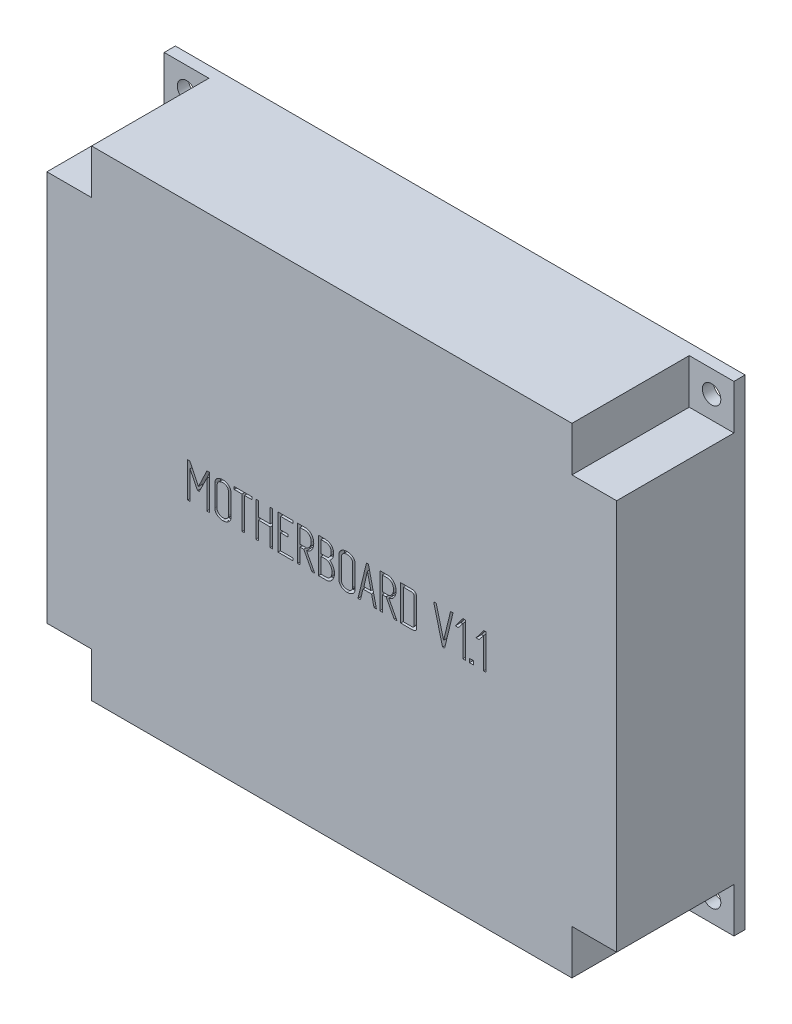
SolidWorks part; units mm, degrees
ref_plane "Front Plane" through (0, 0, 0) normal (0, 0, 1) x (1, 0, 0)
ref_plane "Top Plane" through (0, 0, 0) normal (0, 1, 0) x (1, 0, 0)
ref_plane "Right Plane" through (0, 0, 0) normal (1, 0, 0) x (0, 0, -1)
ref_plane "Plane1" through (0, 0, 23) normal (0, 0, 1) x (1, 0, 0)
sketch "Sketch1" plane through (0, 0, 23) normal (0, 0, 1) x (1, 0, 0)
  line L0 (55.1999, 44.7838) -> (30.0513, 44.7838)
  line L1 (30.0513, 40.8858) -> (30.0513, 40.8761)
  line L2 (30.0513, 40.8761) -> (55.1999, 40.8761)
  spline S0 degree 3 poles (30.0513, 40.8858) (30.0513, 42.1851) (30.0513, 43.4844) (30.0513, 44.7838) knots 0.259336 0.259336 0.259336 0.259336 0.499071 0.499071 0.499071 0.499071
  spline S1 degree 3 poles (55.1999, 44.7838) (55.1999, 43.4812) (55.1999, 42.1787) (55.1999, 40.8761) knots 0.759666 0.759666 0.759666 0.759666 1 1 1 1
extrude "Boss-Extrude1" add sketch "Sketch1" against normal blind 1
sketch "Sketch2" plane through (0, 0, 22) normal (0, 0, -1) x (-1, 0, 0)
  line L0 (-30.0513, 44.7838) -> (-30.0513, 40.8761)
  line L1 (-30.0513, 40.8761) -> (-55.1999, 40.8761)
  line L2 (-55.1999, 40.8761) -> (-55.1999, 44.7838)
  line L3 (-55.1999, 44.7838) -> (-30.0513, 44.7838)
extrude "Boss-Extrude2" add sketch "Sketch2" along normal blind 22
sketch "Sketch3" plane through (0, 44.7838, 0) normal (0, 1, 0) x (-1, 0, 0)
  line L0 (-55.1999, 23) -> (-30.0513, 23)
  line L1 (-30.0513, 23) -> (-30.0513, 0)
  line L2 (-30.0513, 0) -> (-55.1999, 0)
  line L3 (-55.1999, 0) -> (-55.1999, 23)
extrude "Boss-Extrude3" add sketch "Sketch3" along normal blind 1.1962
sketch "Sketch4" plane through (0, 40.8761, 0) normal (0, -1, 0) x (1, 0, 0)
  line L0 (30.0513, 23) -> (55.1999, 23)
  line L1 (55.1999, 23) -> (55.1999, 0)
  line L2 (55.1999, 0) -> (30.0513, 0)
  line L3 (30.0513, 0) -> (30.0513, 23)
extrude "Boss-Extrude4" add sketch "Sketch4" along normal blind 1.2185
sketch "Sketch5" plane through (0, 0, 23) normal (0, 0, 1) x (1, 0, 0)
  line L0 (31.4888, 39.6576) -> (31.545, 39.6576)
  line L1 (31.8363, 45.98) -> (31.1875, 45.98)
  spline S0 degree 3 poles (31.8363, 45.98) (32.0783, 45.9341) (32.298, 45.8314) (32.4985, 45.6785) (32.8054, 45.4444) (32.9531, 45.1417) (32.9531, 44.7838) (32.9531, 43.4812) (32.9531, 42.1787) (32.9531, 40.8761) (32.9531, 40.5134) (32.8032, 40.2135) (32.4985, 39.9814) (32.2203, 39.7694) (31.9055, 39.6628) (31.545, 39.6576) knots 0.649922 0.649922 0.649922 0.649922 0.695537 0.695537 0.695537 0.759638 0.759638 0.759638 1 1 1 1.064152 1.064152 1.064152 1.128028 1.128028 1.128028 1.128028
  spline S1 degree 3 poles (30.0513, 44.7838) (30.0513, 45.1755) (30.2109, 45.4899) (30.535, 45.722) (30.7214, 45.8555) (30.9397, 45.94) (31.1875, 45.98) knots 0.499071 0.499071 0.499071 0.499071 0.566736 0.566736 0.566736 0.611656 0.611656 0.611656 0.611656
  spline S2 degree 3 poles (30.0513, 40.8858) (30.0513, 42.1851) (30.0513, 43.4844) (30.0513, 44.7838) knots 0.259336 0.259336 0.259336 0.259336 0.499071 0.499071 0.499071 0.499071
  spline S3 degree 3 poles (31.4888, 39.6576) (31.1323, 39.6628) (30.8081, 39.7694) (30.5253, 39.9862) (30.2105, 40.2275) (30.0513, 40.5279) (30.0513, 40.8858) knots 0.131331 0.131331 0.131331 0.131331 0.194377 0.194377 0.194377 0.259336 0.259336 0.259336 0.259336
extrude "Cut-Extrude1" cut sketch "Sketch5" against normal blind 1
sketch "Sketch6" plane through (0, 0, 22) normal (0, 0, 1) x (1, 0, 0)
  spline S0 degree 3 poles (30.4866, 44.6967) (30.4866, 43.4522) (30.4866, 42.2077) (30.4866, 40.9631) (30.4866, 40.6971) (30.6172, 40.4795) (30.8783, 40.3151) (31.0918, 40.1807) (31.3088, 40.112) (31.7682, 40.112) (31.981, 40.1748) (32.1696, 40.3102) (32.3897, 40.4683) (32.4985, 40.6826) (32.4985, 40.9631) knots 0.500912 0.500912 0.500912 0.500912 0.780616 0.780616 0.780616 0.840072 0.840072 0.840072 0.890947 0.890947 0.942906 0.942906 0.942906 1 1 1 1
  spline S1 degree 3 poles (32.4985, 40.9631) (32.4985, 42.2061) (32.4985, 43.449) (32.4985, 44.6919) (32.4985, 44.9482) (32.4018, 45.161) (32.2083, 45.3206) (32.023, 45.4735) (31.8021, 45.5527) (31.2894, 45.5527) (31.0718, 45.4947) (30.8832, 45.3835) (30.6196, 45.228) (30.4866, 44.9966) (30.4866, 44.6967) knots 0 0 0 0 0.279282 0.279282 0.279282 0.332989 0.332989 0.332989 0.387747 0.387747 0.438522 0.438522 0.438522 0.500912 0.500912 0.500912 0.500912
extrude "Boss-Extrude5" add sketch "Sketch6" along normal blind 1
sketch "Sketch7" plane through (0, 0, 23) normal (0, 0, 1) x (1, 0, 0)
  spline S0 degree 3 poles (45.3097, 42.4624) (45.1582, 42.4624) (45.0066, 42.4624) (44.8551, 42.4624) knots 0.303115 0.303115 0.303115 0.303115 0.3227 0.3227 0.3227 0.3227
  spline S1 degree 3 poles (45.9916, 42.4624) (45.7643, 42.4624) (45.537, 42.4624) (45.3097, 42.4624) knots 0.155394 0.155394 0.155394 0.155394 0.184772 0.184772 0.184772 0.184772
  spline S2 degree 3 poles (47.4473, 39.7154) (46.9621, 40.6311) (46.4769, 41.5467) (45.9916, 42.4624) knots 0.02146 0.02146 0.02146 0.02146 0.155394 0.155394 0.155394 0.155394
  spline S3 degree 3 poles (47.9455, 39.7154) (47.7794, 39.7154) (47.6134, 39.7154) (47.4473, 39.7154) knots 0 0 0 0 0.02146 0.02146 0.02146 0.02146
  spline S4 degree 3 poles (46.4898, 42.4914) (46.975, 41.5661) (47.4602, 40.6407) (47.9455, 39.7154) knots 0.86496 0.86496 0.86496 0.86496 1 1 1 1
  spline S5 degree 3 poles (44.8551, 45.9638) (45.342, 45.9638) (45.8288, 45.9638) (46.3157, 45.9638) (46.4801, 45.9638) (46.6397, 45.93) (46.7993, 45.8623) (47.4459, 45.588) (47.7762, 45.0498) (47.7762, 43.8359) (47.6601, 43.4635) (47.4328, 43.1249) (47.1839, 42.7541) (46.8718, 42.5446) (46.4898, 42.4914) knots 0.59189 0.59189 0.59189 0.59189 0.654813 0.654813 0.654813 0.676249 0.676249 0.676249 0.768188 0.768188 0.814433 0.814433 0.814433 0.86496 0.86496 0.86496 0.86496
  spline S6 degree 3 poles (44.8551, 42.4624) (44.8551, 43.6295) (44.8551, 44.7967) (44.8551, 45.9638) knots 0.441044 0.441044 0.441044 0.441044 0.59189 0.59189 0.59189 0.59189
extrude "Cut-Extrude2" cut sketch "Sketch7" against normal blind 1
sketch "Sketch8" plane through (0, 0, 23) normal (0, 0, 1) x (1, 0, 0)
  line L0 (53.7352, 39.6576) -> (53.7914, 39.6576)
  line L1 (54.0828, 45.98) -> (53.4321, 45.98)
  spline S0 degree 3 poles (55.1999, 40.8761) (55.1999, 40.5134) (55.0451, 40.2135) (54.7404, 39.9814) (54.4651, 39.7716) (54.152, 39.6629) (53.7914, 39.6576) knots 0 0 0 0 0.064284 0.064284 0.064284 0.12763 0.12763 0.12763 0.12763
  spline S1 degree 3 poles (55.1999, 44.7838) (55.1999, 43.4812) (55.1999, 42.1787) (55.1999, 40.8761) knots 0.759666 0.759666 0.759666 0.759666 1 1 1 1
  spline S2 degree 3 poles (54.0828, 45.98) (54.3246, 45.9341) (54.5433, 45.8314) (54.7404, 45.6785) (55.0454, 45.4419) (55.1999, 45.1417) (55.1999, 44.7838) knots 0.65 0.65 0.65 0.65 0.695442 0.695442 0.695442 0.759666 0.759666 0.759666 0.759666
  spline S3 degree 3 poles (53.7352, 39.6576) (53.3744, 39.6628) (53.0549, 39.7694) (52.7721, 39.9862) (52.4543, 40.2299) (52.2933, 40.5279) (52.2933, 40.8858) (52.2933, 42.1851) (52.2933, 43.4844) (52.2933, 44.7838) (52.2933, 45.1755) (52.4577, 45.4899) (52.7817, 45.722) (52.9681, 45.8555) (53.1841, 45.94) (53.4321, 45.98) knots 0.130908 0.130908 0.130908 0.130908 0.194235 0.194235 0.194235 0.259381 0.259381 0.259381 0.499095 0.499095 0.499095 0.566888 0.566888 0.566888 0.611816 0.611816 0.611816 0.611816
extrude "Cut-Extrude3" cut sketch "Sketch8" against normal blind 1
sketch "Sketch9" plane through (0, 0, 22) normal (0, 0, 1) x (1, 0, 0)
  spline S0 degree 3 poles (47.3216, 44.2373) (47.3216, 44.6339) (47.2007, 44.953) (46.9637, 45.1997) (46.767, 45.4045) (46.543, 45.5092) (46.2866, 45.5092) (45.961, 45.5092) (45.6354, 45.5092) (45.3097, 45.5092) knots 0 0 0 0 0.128122 0.128122 0.128122 0.221363 0.221363 0.221363 0.340085 0.340085 0.340085 0.340085
  spline S1 degree 3 poles (45.3097, 42.917) (45.6612, 42.917) (46.0126, 42.917) (46.364, 42.917) (46.5575, 42.917) (46.7558, 43.0234) (46.954, 43.241) (47.1935, 43.5039) (47.3216, 43.831) (47.3216, 44.2373) knots 0.655269 0.655269 0.655269 0.655269 0.78346 0.78346 0.78346 0.867722 0.867722 0.867722 1 1 1 1
  spline S2 degree 3 poles (45.3097, 45.5092) (45.3097, 44.6451) (45.3097, 43.7811) (45.3097, 42.917) knots 0.340085 0.340085 0.340085 0.340085 0.655269 0.655269 0.655269 0.655269
extrude "Boss-Extrude6" add sketch "Sketch9" along normal blind 1
sketch "Sketch10" plane through (55.1999, 0, 0) normal (1, 0, 0) x (0, 0, -1)
  line L0 (-23, 39.6576) -> (-23, 45.98)
  line L1 (-23, 45.98) -> (0, 45.98)
  line L2 (0, 45.98) -> (0, 39.6576)
  line L3 (0, 39.6576) -> (-23, 39.6576)
extrude "Boss-Extrude7" add sketch "Sketch10" along normal blind 46.8001
sketch "Sketch11" plane through (0, 0, 23) normal (0, 0, 1) x (1, 0, 0)
  spline S0 degree 3 poles (60.0458, 42.4624) (59.8942, 42.4624) (59.7427, 42.4624) (59.5912, 42.4624) knots 0.303165 0.303165 0.303165 0.303165 0.322754 0.322754 0.322754 0.322754
  spline S1 degree 3 poles (60.7277, 42.4624) (60.5004, 42.4624) (60.2731, 42.4624) (60.0458, 42.4624) knots 0.15542 0.15542 0.15542 0.15542 0.184802 0.184802 0.184802 0.184802
  spline S2 degree 3 poles (62.1834, 39.7154) (61.6982, 40.6311) (61.2129, 41.5467) (60.7277, 42.4624) knots 0.021464 0.021464 0.021464 0.021464 0.15542 0.15542 0.15542 0.15542
  spline S3 degree 3 poles (62.6815, 39.7154) (62.5155, 39.7154) (62.3494, 39.7154) (62.1834, 39.7154) knots 0 0 0 0 0.021464 0.021464 0.021464 0.021464
  spline S4 degree 3 poles (61.2258, 42.4914) (61.7111, 41.5661) (62.1963, 40.6407) (62.6815, 39.7154) knots 0.864938 0.864938 0.864938 0.864938 1 1 1 1
  spline S5 degree 3 poles (59.5912, 45.9638) (60.078, 45.9638) (60.5649, 45.9638) (61.0517, 45.9638) (61.2162, 45.9638) (61.3758, 45.93) (61.5353, 45.8623) (62.1819, 45.588) (62.5074, 45.0498) (62.5074, 43.8359) (62.3962, 43.4635) (62.1689, 43.1249) (61.9199, 42.7541) (61.6079, 42.5446) (61.2258, 42.4914) knots 0.591988 0.591988 0.591988 0.591988 0.654921 0.654921 0.654921 0.676361 0.676361 0.676361 0.768205 0.768205 0.814402 0.814402 0.814402 0.864938 0.864938 0.864938 0.864938
  spline S6 degree 3 poles (59.5912, 42.4624) (59.5912, 43.6295) (59.5912, 44.7967) (59.5912, 45.9638) knots 0.441117 0.441117 0.441117 0.441117 0.591988 0.591988 0.591988 0.591988
extrude "Cut-Extrude4" cut sketch "Sketch11" against normal blind 1
sketch "Sketch12" plane through (0, 39.6576, 0) normal (0, -1, 0) x (1, 0, 0)
  line L0 (30.0513, 23) -> (102, 23)
  line L1 (102, 23) -> (102, 0)
  line L2 (102, 0) -> (30.0513, 0)
  line L3 (30.0513, 0) -> (30.0513, 23)
extrude "Boss-Extrude8" add sketch "Sketch12" along normal blind 39.6576
sketch "Sketch13" plane through (30.0513, 0, 0) normal (-1, 0, 0) x (0, 0, 1)
  line L0 (23, 45.98) -> (23, 0)
  line L1 (23, 0) -> (0, 0)
  line L2 (0, 0) -> (0, 45.98)
  line L3 (0, 45.98) -> (23, 45.98)
extrude "Boss-Extrude9" add sketch "Sketch13" along normal blind 30.0513
sketch "Sketch14" plane through (0, 45.98, 0) normal (0, 1, 0) x (-1, 0, 0)
  line L0 (-102, 23) -> (0, 23)
  line L1 (0, 23) -> (0, 0)
  line L2 (0, 0) -> (-102, 0)
  line L3 (-102, 0) -> (-102, 23)
extrude "Boss-Extrude10" add sketch "Sketch14" along normal blind 40.02
sketch "Sketch15" plane through (0, 42.4624, 0) normal (0, 1, 0) x (-1, 0, 0)
  line L0 (-45.3097, 23) -> (-45.3097, 22)
  line L1 (-44.8551, 22) -> (-44.8551, 23)
  spline S0 degree 3 poles (-45.3097, 23) (-45.1582, 23) (-45.0066, 23) (-44.8551, 23) knots 0.303115 0.303115 0.303115 0.303115 0.3227 0.3227 0.3227 0.3227
  spline S1 degree 3 poles (-45.3097, 22) (-45.1582, 22) (-45.0066, 22) (-44.8551, 22) knots 0.303115 0.303115 0.303115 0.303115 0.3227 0.3227 0.3227 0.3227
extrude "Cut-Extrude5" cut sketch "Sketch15" against normal blind 2.747
sketch "Sketch16" plane through (0, 42.4624, 0) normal (0, 1, 0) x (-1, 0, 0)
  line L0 (-60.0458, 23) -> (-60.0458, 22)
  line L1 (-59.5912, 22) -> (-59.5912, 23)
  spline S0 degree 3 poles (-60.0458, 23) (-59.8942, 23) (-59.7427, 23) (-59.5912, 23) knots 0.303165 0.303165 0.303165 0.303165 0.322754 0.322754 0.322754 0.322754
  spline S1 degree 3 poles (-60.0458, 22) (-59.8942, 22) (-59.7427, 22) (-59.5912, 22) knots 0.303165 0.303165 0.303165 0.303165 0.322754 0.322754 0.322754 0.322754
extrude "Cut-Extrude6" cut sketch "Sketch16" against normal blind 2.747
sketch "Sketch17" plane through (0, 0, 22) normal (0, 0, 1) x (1, 0, 0)
  spline S0 degree 3 poles (62.0577, 44.2373) (62.0577, 44.6339) (61.9368, 44.953) (61.6998, 45.1997) (61.503, 45.4045) (61.279, 45.5092) (61.0179, 45.5092) (60.6938, 45.5092) (60.3698, 45.5092) (60.0458, 45.5092) knots 0 0 0 0 0.128125 0.128125 0.128125 0.221934 0.221934 0.221934 0.340071 0.340071 0.340071 0.340071
  spline S1 degree 3 poles (60.0458, 42.917) (60.3972, 42.917) (60.7487, 42.917) (61.1001, 42.917) (61.2935, 42.917) (61.4918, 43.0234) (61.6901, 43.241) (61.9296, 43.5039) (62.0577, 43.831) (62.0577, 44.2373) knots 0.655262 0.655262 0.655262 0.655262 0.783455 0.783455 0.783455 0.867719 0.867719 0.867719 1 1 1 1
  spline S2 degree 3 poles (60.0458, 45.5092) (60.0458, 44.6451) (60.0458, 43.7811) (60.0458, 42.917) knots 0.340071 0.340071 0.340071 0.340071 0.655262 0.655262 0.655262 0.655262
extrude "Boss-Extrude11" add sketch "Sketch17" along normal blind 1
sketch "Sketch18" plane through (0, 0, 23) normal (0, 0, 1) x (1, 0, 0)
  spline S0 degree 3 poles (51.5001, 41.4661) (51.5001, 41.0744) (51.3792, 40.6923) (51.1326, 40.3248) (50.8545, 39.9104) (50.528, 39.7009) (50.146, 39.7009) (49.6382, 39.7009) (49.1304, 39.7009) (48.6226, 39.7009) knots 0 0 0 0 0.070495 0.070495 0.070495 0.14111 0.14111 0.14111 0.229318 0.229318 0.229318 0.229318
  spline S1 degree 3 poles (50.678, 43.0766) (51.2293, 42.6268) (51.5001, 42.09) (51.5001, 41.4661) knots 0.891487 0.891487 0.891487 0.891487 1 1 1 1
  spline S2 degree 3 poles (48.6226, 45.9638) (48.9305, 45.9638) (49.2384, 45.9638) (49.5463, 45.9638) (50.4361, 45.9638) (50.9972, 45.6688) (51.2293, 45.0836) (51.3045, 44.8941) (51.3454, 44.6871) (51.3454, 44.1696) (51.2825, 43.9181) (51.1616, 43.7053) (51.0931, 43.5848) (50.9343, 43.3764) (50.678, 43.0766) knots 0.592032 0.592032 0.592032 0.592032 0.645529 0.645529 0.645529 0.763043 0.763043 0.763043 0.798492 0.798492 0.8455 0.8455 0.8455 0.891487 0.891487 0.891487 0.891487
  spline S3 degree 3 poles (48.6226, 39.7009) (48.6226, 41.7885) (48.6226, 43.8762) (48.6226, 45.9638) knots 0.229318 0.229318 0.229318 0.229318 0.592032 0.592032 0.592032 0.592032
extrude "Cut-Extrude7" cut sketch "Sketch18" against normal blind 1
sketch "Sketch19" plane through (0, 0, 22) normal (0, 0, 1) x (1, 0, 0)
  spline S0 degree 3 poles (49.0772, 40.141) (49.398, 40.141) (49.7188, 40.141) (50.0396, 40.141) (50.3491, 40.141) (50.6006, 40.2861) (50.7989, 40.5859) (50.9668, 40.8399) (51.0455, 41.1372) (51.0455, 41.4709) knots 0.665553 0.665553 0.665553 0.665553 0.779877 0.779877 0.779877 0.88925 0.88925 0.88925 1 1 1 1
  spline S1 degree 3 poles (49.0772, 42.9025) (49.0772, 41.982) (49.0772, 41.0615) (49.0772, 40.141) knots 0.337518 0.337518 0.337518 0.337518 0.665553 0.665553 0.665553 0.665553
  spline S2 degree 3 poles (51.0455, 41.4709) (51.0455, 41.7805) (50.944, 42.09) (50.7408, 42.3947) (50.5146, 42.734) (50.2524, 42.9025) (49.9477, 42.9025) (49.6575, 42.9025) (49.3673, 42.9025) (49.0772, 42.9025) knots 0 0 0 0 0.11726 0.11726 0.11726 0.234094 0.234094 0.234094 0.337518 0.337518 0.337518 0.337518
extrude "Boss-Extrude12" add sketch "Sketch19" along normal blind 1
sketch "Sketch20" plane through (0, 0, 22) normal (0, 0, 1) x (1, 0, 0)
  spline S0 degree 3 poles (49.0772, 43.3281) (49.4205, 43.3281) (49.7639, 43.3281) (50.1073, 43.3281) (50.3394, 43.3281) (50.528, 43.4586) (50.6876, 43.7246) (50.8259, 43.9551) (50.8908, 44.1938) (50.8908, 44.4404) knots 0.648055 0.648055 0.648055 0.648055 0.791827 0.791827 0.791827 0.894843 0.894843 0.894843 1 1 1 1
  spline S1 degree 3 poles (49.0772, 45.5092) (49.0772, 44.7822) (49.0772, 44.0551) (49.0772, 43.3281) knots 0.343634 0.343634 0.343634 0.343634 0.648055 0.648055 0.648055 0.648055
  spline S2 degree 3 poles (50.8908, 44.4404) (50.8908, 45.1513) (50.5039, 45.5092) (49.7252, 45.5092) (49.5092, 45.5092) (49.2932, 45.5092) (49.0772, 45.5092) knots 0 0 0 0 0.253186 0.253186 0.253186 0.343634 0.343634 0.343634 0.343634
extrude "Boss-Extrude13" add sketch "Sketch20" along normal blind 1
sketch "Sketch21" plane through (0, 0, 23) normal (0, 0, 1) x (1, 0, 0)
  spline S0 degree 1 poles (59.0012, 39.7154) (58.5659, 39.7154) knots 0 0 0.02236 0.02236
  spline S1 degree 1 poles (57.5599, 45.9638) (59.0012, 39.7154) knots 0.670587 0.670587 1 1
  spline S2 degree 1 poles (57.2166, 45.9638) (57.5599, 45.9638) knots 0.652948 0.652948 0.670587 0.670587
  spline S3 degree 1 poles (55.6932, 39.7154) (57.2166, 45.9638) knots 0.32256 0.32256 0.652948 0.652948
  spline S4 degree 1 poles (56.1333, 39.7154) (55.6932, 39.7154) knots 0.299952 0.299952 0.32256 0.32256
  spline S5 degree 1 poles (56.5927, 41.6015) (56.1333, 39.7154) knots 0.200227 0.200227 0.299952 0.299952
  spline S6 degree 1 poles (58.1161, 41.6015) (56.5927, 41.6015) knots 0.121968 0.121968 0.200227 0.200227
  spline S7 degree 1 poles (58.5659, 39.7154) (58.1161, 41.6015) knots 0.02236 0.02236 0.121968 0.121968
extrude "Cut-Extrude8" cut sketch "Sketch21" against normal blind 1
sketch "Sketch22" plane through (0, 0, 22) normal (0, 0, 1) x (1, 0, 0)
  spline S0 degree 1 poles (56.762, 42.0513) (58.0097, 42.0513) knots 0.817936 0.817936 1 1
  spline S1 degree 1 poles (57.381, 44.7838) (56.762, 42.0513) knots 0.409125 0.409125 0.817936 0.817936
  spline S2 degree 1 poles (58.0097, 42.0513) (57.381, 44.7838) knots 0 0 0.409125 0.409125
extrude "Boss-Extrude14" add sketch "Sketch22" along normal blind 1
sketch "Sketch23" plane through (0, 0, 23) normal (0, 0, 1) x (1, 0, 0)
  spline S0 degree 3 poles (66.2072, 40.3054) (66.2072, 40.1216) (66.125, 39.9765) (65.9557, 39.8605) (65.8008, 39.7543) (65.6317, 39.7009) (65.443, 39.7009) (64.7434, 39.7009) (64.0438, 39.7009) (63.3441, 39.7009) knots 0 0 0 0 0.030295 0.030295 0.030295 0.061235 0.061235 0.061235 0.18029 0.18029 0.18029 0.18029
  spline S1 degree 3 poles (65.6365, 45.9203) (66.0186, 45.8187) (66.2072, 45.5624) (66.2072, 45.1562) (66.2072, 43.5393) (66.2072, 41.9223) (66.2072, 40.3054) knots 0.665828 0.665828 0.665828 0.665828 0.724855 0.724855 0.724855 1 1 1 1
  spline S2 degree 3 poles (63.3441, 45.9638) (63.9728, 45.9638) (64.6015, 45.9638) (65.2302, 45.9638) (65.443, 45.9638) (65.5785, 45.9493) (65.6365, 45.9203) knots 0.535537 0.535537 0.535537 0.535537 0.642523 0.642523 0.642523 0.665828 0.665828 0.665828 0.665828
  spline S3 degree 3 poles (63.3441, 39.7009) (63.3441, 41.7885) (63.3441, 43.8762) (63.3441, 45.9638) knots 0.18029 0.18029 0.18029 0.18029 0.535537 0.535537 0.535537 0.535537
extrude "Cut-Extrude9" cut sketch "Sketch23" against normal blind 1
sketch "Sketch24" plane through (0, 0, 22) normal (0, 0, 1) x (1, 0, 0)
  spline S0 degree 3 poles (63.7987, 40.141) (64.2823, 40.141) (64.766, 40.141) (65.2496, 40.141) (65.5881, 40.141) (65.7526, 40.257) (65.7526, 40.4989) knots 0.849256 0.849256 0.849256 0.849256 0.950746 0.950746 0.950746 1 1 1 1
  spline S1 degree 3 poles (63.7987, 45.5092) (63.7987, 43.7198) (63.7987, 41.9304) (63.7987, 40.141) knots 0.473743 0.473743 0.473743 0.473743 0.849256 0.849256 0.849256 0.849256
  spline S2 degree 3 poles (65.7526, 40.4989) (65.7526, 42.0045) (65.7526, 43.5102) (65.7526, 45.0159) (65.7526, 45.3448) (65.5785, 45.5092) (65.2254, 45.5092) (64.7498, 45.5092) (64.2743, 45.5092) (63.7987, 45.5092) knots 0 0 0 0 0.315972 0.315972 0.315972 0.373945 0.373945 0.373945 0.473743 0.473743 0.473743 0.473743
extrude "Boss-Extrude15" add sketch "Sketch24" along normal blind 1
sketch "Sketch25" plane through (0, 0, 22) normal (0, 0, 1) x (1, 0, 0)
  spline S0 degree 3 poles (52.7334, 44.6967) (52.7334, 43.4522) (52.7334, 42.2077) (52.7334, 40.9631) (52.7334, 40.6971) (52.8639, 40.4795) (53.1251, 40.3151) (53.3385, 40.1807) (53.5555, 40.112) (54.015, 40.112) (54.2229, 40.1748) (54.4115, 40.3102) (54.6317, 40.4683) (54.7452, 40.6826) (54.7452, 40.9631) knots 0.501007 0.501007 0.501007 0.501007 0.780735 0.780735 0.780735 0.840197 0.840197 0.840197 0.890921 0.890921 0.942725 0.942725 0.942725 1 1 1 1
  spline S1 degree 3 poles (54.7452, 40.9631) (54.7452, 42.2061) (54.7452, 43.449) (54.7452, 44.6919) (54.7452, 44.9482) (54.6485, 45.161) (54.4502, 45.3206) (54.2661, 45.4689) (54.0488, 45.5527) (53.5313, 45.5527) (53.3137, 45.4947) (53.1299, 45.3835) (52.8646, 45.2229) (52.7334, 44.9966) (52.7334, 44.6967) knots 0 0 0 0 0.279381 0.279381 0.279381 0.333327 0.333327 0.333327 0.387406 0.387406 0.438536 0.438536 0.438536 0.501007 0.501007 0.501007 0.501007
extrude "Boss-Extrude16" add sketch "Sketch25" along normal blind 1
sketch "Sketch26" plane through (0, 0, 23) normal (0, 0, 1) x (1, 0, 0)
  spline S0 degree 1 poles (29.0696, 39.7009) (28.6198, 39.7009) knots 0 0 0.011909 0.011909
  spline S1 degree 1 poles (29.0696, 45.9638) (29.0696, 39.7009) knots 0.834175 0.834175 1 1
  spline S2 degree 1 poles (28.644, 45.9542) (29.0696, 45.9638) knots 0.822904 0.822904 0.834175 0.834175
  spline S3 degree 1 poles (27.1399, 42.7719) (28.644, 45.9542) knots 0.72971 0.72971 0.822904 0.822904
  spline S4 degree 1 poles (25.5875, 45.9542) (27.1399, 42.7719) knots 0.635962 0.635962 0.72971 0.72971
  spline S5 degree 1 poles (25.1764, 45.9638) (25.5875, 45.9542) knots 0.625074 0.625074 0.635962 0.635962
  spline S6 degree 1 poles (25.1764, 39.7009) (25.1764, 45.9638) knots 0.45925 0.45925 0.625074 0.625074
  spline S7 degree 1 poles (25.631, 39.7009) (25.1764, 39.7009) knots 0.447213 0.447213 0.45925 0.45925
  spline S8 degree 1 poles (25.631, 44.7548) (25.631, 39.7009) knots 0.313401 0.313401 0.447213 0.447213
  spline S9 degree 1 poles (27.1229, 41.7549) (26.9706, 42.061) (25.631, 44.7548) knots 0.224694 0.224694 0.233744 0.313401 0.313401
  spline S10 degree 1 poles (28.6198, 44.7596) (27.2753, 42.061) (27.1229, 41.7549) knots 0.145849 0.145849 0.225677 0.234731 0.234731
  spline S11 degree 1 poles (28.6198, 39.7009) (28.6198, 44.7596) knots 0.011909 0.011909 0.145849 0.145849
extrude "Cut-Extrude10" cut sketch "Sketch26" against normal blind 1
sketch "Sketch27" plane through (0, 0, 23) normal (0, 0, 1) x (1, 0, 0)
  spline S0 degree 1 poles (40.4348, 39.7154) (39.9802, 39.7154) knots 0 0 0.015079 0.015079
  spline S1 degree 1 poles (40.4348, 45.9638) (40.4348, 39.7154) knots 0.792749 0.792749 1 1
  spline S2 degree 1 poles (39.9802, 45.9638) (40.4348, 45.9638) knots 0.777671 0.777671 0.792749 0.792749
  spline S3 degree 1 poles (39.9802, 43.3861) (39.9802, 45.9638) knots 0.692172 0.692172 0.777671 0.777671
  spline S4 degree 1 poles (37.8571, 43.3861) (39.9802, 43.3861) knots 0.621752 0.621752 0.692172 0.692172
  spline S5 degree 1 poles (37.8571, 45.9638) (37.8571, 43.3861) knots 0.536253 0.536253 0.621752 0.621752
  spline S6 degree 1 poles (37.4024, 45.9638) (37.8571, 45.9638) knots 0.521174 0.521174 0.536253 0.536253
  spline S7 degree 1 poles (37.4024, 39.7154) (37.4024, 45.9638) knots 0.313924 0.313924 0.521174 0.521174
  spline S8 degree 1 poles (37.8571, 39.7154) (37.4024, 39.7154) knots 0.298845 0.298845 0.313924 0.313924
  spline S9 degree 1 poles (37.8571, 42.9315) (37.8571, 39.7154) knots 0.192172 0.192172 0.298845 0.298845
  spline S10 degree 1 poles (39.9802, 42.9315) (37.8571, 42.9315) knots 0.121752 0.121752 0.192172 0.192172
  spline S11 degree 1 poles (39.9802, 39.7154) (39.9802, 42.9315) knots 0.015079 0.015079 0.121752 0.121752
extrude "Cut-Extrude11" cut sketch "Sketch27" against normal blind 1
sketch "Sketch28" plane through (0, 0, 23) normal (0, 0, 1) x (1, 0, 0)
  spline S0 degree 1 poles (44.0184, 39.7154) (41.3827, 39.7154) knots 0 0 0.106196 0.106196
  spline S1 degree 1 poles (44.0184, 40.141) (44.0184, 39.7154) knots 0.982853 0.982853 1 1
  spline S2 degree 1 poles (41.8373, 40.141) (44.0184, 40.141) knots 0.894973 0.894973 0.982853 0.982853
  spline S3 degree 1 poles (41.8373, 42.946) (41.8373, 40.141) knots 0.781956 0.781956 0.894973 0.894973
  spline S4 degree 1 poles (43.1963, 42.946) (41.8373, 42.946) knots 0.727202 0.727202 0.781956 0.781956
  spline S5 degree 1 poles (43.1963, 43.3861) (43.1963, 42.946) knots 0.70947 0.70947 0.727202 0.727202
  spline S6 degree 1 poles (41.8373, 43.3861) (43.1963, 43.3861) knots 0.654716 0.654716 0.70947 0.70947
  spline S7 degree 1 poles (41.8373, 45.4947) (41.8373, 43.3861) knots 0.569758 0.569758 0.654716 0.654716
  spline S8 degree 1 poles (44.0184, 45.4947) (41.8373, 45.4947) knots 0.481878 0.481878 0.569758 0.569758
  spline S9 degree 1 poles (44.0184, 45.9493) (44.0184, 45.4947) knots 0.463562 0.463562 0.481878 0.481878
  spline S10 degree 1 poles (41.3827, 45.9493) (44.0184, 45.9493) knots 0.357366 0.357366 0.463562 0.463562
  spline S11 degree 1 poles (41.3827, 39.7154) (41.3827, 45.9493) knots 0.106196 0.106196 0.357366 0.357366
extrude "Cut-Extrude12" cut sketch "Sketch28" against normal blind 1
sketch "Sketch29" plane through (0, 0, 23) normal (0, 0, 1) x (1, 0, 0)
  spline S0 degree 1 poles (36.7496, 45.5092) (35.3761, 45.5092) knots 0 0 0.072449 0.072449
  spline S1 degree 1 poles (36.7496, 45.9638) (36.7496, 45.5092) knots 0.97602 0.97602 1 1
  spline S2 degree 1 poles (33.5334, 45.9638) (36.7496, 45.9638) knots 0.806378 0.806378 0.97602 0.97602
  spline S3 degree 1 poles (33.5334, 45.5092) (33.5334, 45.9638) knots 0.782398 0.782398 0.806378 0.806378
  spline S4 degree 1 poles (34.936, 45.5092) (33.5334, 45.5092) knots 0.708418 0.708418 0.782398 0.782398
  spline S5 degree 1 poles (34.936, 39.7009) (34.936, 45.5092) knots 0.402041 0.402041 0.708418 0.708418
  spline S6 degree 1 poles (35.3761, 39.7009) (34.936, 39.7009) knots 0.378827 0.378827 0.402041 0.402041
  spline S7 degree 1 poles (35.3761, 45.5092) (35.3761, 39.7009) knots 0.072449 0.072449 0.378827 0.378827
extrude "Cut-Extrude13" cut sketch "Sketch29" against normal blind 1
sketch "Sketch30" plane through (0, 0, 23) normal (0, 0, 1) x (1, 0, 0)
  spline S0 degree 1 poles (72.7119, 45.9638) (71.1982, 39.7154) knots 0 0 0.261082 0.261082
  spline S1 degree 1 poles (72.2622, 45.9638) (72.7119, 45.9638) knots 0.981735 0.981735 1 1
  spline S2 degree 1 poles (71.0289, 40.8858) (72.2622, 45.9638) knots 0.769527 0.769527 0.981735 0.981735
  spline S3 degree 1 poles (69.6941, 45.9638) (71.0289, 40.8858) knots 0.556308 0.556308 0.769527 0.769527
  spline S4 degree 1 poles (69.2395, 45.9638) (69.6941, 45.9638) knots 0.537847 0.537847 0.556308 0.556308
  spline S5 degree 1 poles (70.8306, 39.7154) (69.2395, 45.9638) knots 0.276008 0.276008 0.537847 0.537847
  spline S6 degree 1 poles (71.1982, 39.7154) (70.8306, 39.7154) knots 0.261082 0.261082 0.276008 0.276008
extrude "Cut-Extrude14" cut sketch "Sketch30" against normal blind 1
sketch "Sketch31" plane through (0, 0, 23) normal (0, 0, 1) x (1, 0, 0)
  spline S0 degree 1 poles (74.9076, 39.7009) (74.453, 39.7057) knots 0 0 0.027142 0.027142
  spline S1 degree 1 poles (74.9076, 45.9783) (74.9076, 39.7009) knots 0.625229 0.625229 1 1
  spline S2 degree 1 poles (74.4917, 45.9783) (74.9076, 45.9783) knots 0.600399 0.600399 0.625229 0.625229
  spline S3 degree 1 poles (73.1085, 44.1551) (74.4917, 45.9783) knots 0.46377 0.46377 0.600399 0.600399
  spline S4 degree 1 poles (73.6598, 44.1551) (73.1085, 44.1551) knots 0.430855 0.430855 0.46377 0.46377
  spline S5 degree 1 poles (74.453, 45.1755) (73.6598, 44.1551) knots 0.353695 0.353695 0.430855 0.430855
  spline S6 degree 1 poles (74.453, 39.7057) (74.453, 45.1755) knots 0.027142 0.027142 0.353695 0.353695
extrude "Cut-Extrude15" cut sketch "Sketch31" against normal blind 1
sketch "Sketch32" plane through (0, 0, 23) normal (0, 0, 1) x (1, 0, 0)
  spline S0 degree 1 poles (78.6315, 39.7009) (78.1817, 39.7057) knots 0 0 0.026859 0.026859
  spline S1 degree 1 poles (78.6315, 45.9783) (78.6315, 39.7009) knots 0.625145 0.625145 1 1
  spline S2 degree 1 poles (78.2204, 45.9783) (78.6315, 45.9783) knots 0.600597 0.600597 0.625145 0.625145
  spline S3 degree 1 poles (76.8324, 44.1551) (78.2204, 45.9783) knots 0.463763 0.463763 0.600597 0.600597
  spline S4 degree 1 poles (77.3837, 44.1551) (76.8324, 44.1551) knots 0.430841 0.430841 0.463763 0.463763
  spline S5 degree 1 poles (78.1817, 45.1755) (77.3837, 44.1551) knots 0.353486 0.353486 0.430841 0.430841
  spline S6 degree 1 poles (78.1817, 39.7057) (78.1817, 45.1755) knots 0.026859 0.026859 0.353486 0.353486
extrude "Cut-Extrude16" cut sketch "Sketch32" against normal blind 1
sketch "Sketch33" plane through (0, 0, 23) normal (0, 0, 1) x (1, 0, 0)
  line L0 (0, 0) -> (8, 0)
  line L1 (8, 0) -> (8, 8)
  line L2 (8, 8) -> (0, 8)
  line L3 (0, 8) -> (0, 0)
extrude "Cut-Extrude17" cut sketch "Sketch33" against normal blind 21
sketch "Sketch34" plane through (0, 0, 23) normal (0, 0, 1) x (1, 0, 0)
  line L0 (102, 86) -> (94, 86)
  line L1 (94, 86) -> (94, 78)
  line L2 (94, 78) -> (102, 78)
  line L3 (102, 78) -> (102, 86)
extrude "Cut-Extrude18" cut sketch "Sketch34" against normal blind 21
sketch "Sketch35" plane through (102, 0, 0) normal (1, 0, 0) x (0, 0, -1)
  line L0 (-2, 8) -> (-23, 8)
  line L1 (-23, 8) -> (-23, 0)
  line L2 (-23, 0) -> (-2, 0)
  line L3 (-2, 0) -> (-2, 8)
extrude "Cut-Extrude19" cut sketch "Sketch35" against normal blind 8
sketch "Sketch36" plane through (0, 0, 0) normal (-1, 0, 0) x (0, 0, 1)
  line L0 (2, 78) -> (23, 78)
  line L1 (23, 78) -> (23, 86)
  line L2 (23, 86) -> (2, 86)
  line L3 (2, 86) -> (2, 78)
extrude "Cut-Extrude20" cut sketch "Sketch36" against normal blind 8
sketch "Sketch37" plane through (0, 0, 23) normal (0, 0, 1) x (1, 0, 0)
  spline S0 degree 1 poles (76.3391, 39.7154) (75.6572, 39.7154) knots 0 0 0.25089 0.25089
  spline S1 degree 1 poles (76.3391, 40.3925) (76.3391, 39.7154) knots 0.75089 0.75089 1 1
  spline S2 degree 1 poles (75.6572, 40.3925) (76.3391, 40.3925) knots 0.5 0.5 0.75089 0.75089
  spline S3 degree 1 poles (75.6572, 39.7154) (75.6572, 40.3925) knots 0.25089 0.25089 0.5 0.5
extrude "Cut-Extrude21" cut sketch "Sketch37" against normal blind 1
hole_wizard "Hole1" positions "Sketch39" profile "Sketch38" legacy
sketch "Sketch39" plane through (0, 0, 2) normal (0, 0, 1) x (1, 0, 0)
  point P0 (4, 4)
sketch "Sketch38" plane through (4, 4, 2) normal (1, 0, 0) x (0, -1, 0)
  line L0 (0, 0) -> (0, 2)
  line L1 (0, 2) -> (1.65, 2)
  line L2 (1.65, 2) -> (1.65, 0)
  line L3 (1.65, 0) -> (0, 0)
  line L4 (0, 110) -> (0, -10) construction
  dimension "Diameter" = 3.3
  dimension "Depth" = 2
hole_wizard "Hole2" positions "Sketch41" profile "Sketch40" legacy
sketch "Sketch41" plane through (0, 0, 2) normal (0, 0, 1) x (1, 0, 0)
  point P0 (98, 82)
sketch "Sketch40" plane through (98, 82, 2) normal (1, 0, 0) x (0, -1, 0)
  line L0 (0, 0) -> (0, 2)
  line L1 (0, 2) -> (1.65, 2)
  line L2 (1.65, 2) -> (1.65, 0)
  line L3 (1.65, 0) -> (0, 0)
  line L4 (0, 110) -> (0, -10) construction
  dimension "Diameter" = 3.3
  dimension "Depth" = 2
hole_wizard "Hole3" positions "Sketch43" profile "Sketch42" legacy
sketch "Sketch43" plane through (0, 0, 2) normal (0, 0, 1) x (1, 0, 0)
  point P0 (98, 4)
sketch "Sketch42" plane through (98, 4, 2) normal (1, 0, 0) x (0, -1, 0)
  line L0 (0, 0) -> (0, 2)
  line L1 (0, 2) -> (1.65, 2)
  line L2 (1.65, 2) -> (1.65, 0)
  line L3 (1.65, 0) -> (0, 0)
  line L4 (0, 110) -> (0, -10) construction
  dimension "Diameter" = 3.3
  dimension "Depth" = 2
hole_wizard "Hole4" positions "Sketch45" profile "Sketch44" legacy
sketch "Sketch45" plane through (0, 0, 2) normal (0, 0, 1) x (1, 0, 0)
  point P0 (4, 82)
sketch "Sketch44" plane through (4, 82, 2) normal (1, 0, 0) x (0, -1, 0)
  line L0 (0, 0) -> (0, 2)
  line L1 (0, 2) -> (1.65, 2)
  line L2 (1.65, 2) -> (1.65, 0)
  line L3 (1.65, 0) -> (0, 0)
  line L4 (0, 110) -> (0, -10) construction
  dimension "Diameter" = 3.3
  dimension "Depth" = 2
chamfer "Chamfer1" distance 0.3419 angle 63.517 1 edges at (27.1229, 41.7549, 22.5)
